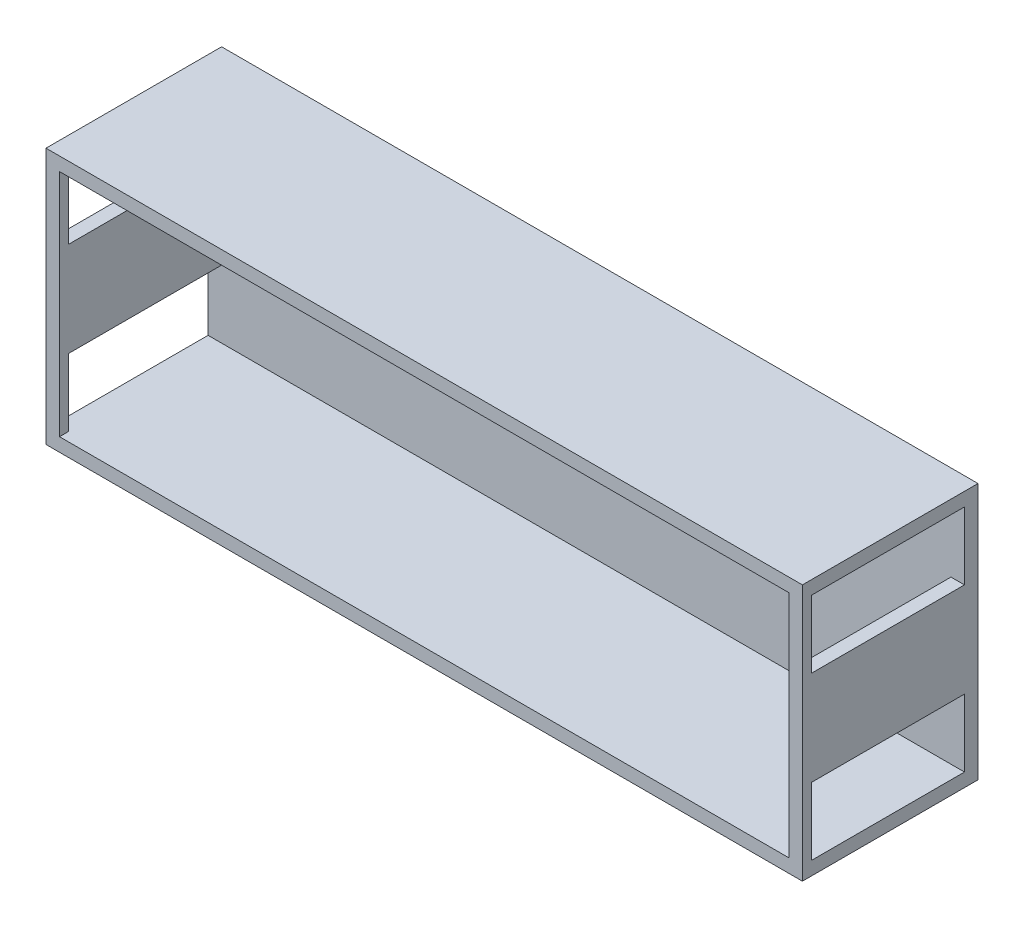
SolidWorks part; units mm, degrees
ref_plane "Front Plane" through (0, 0, 0) normal (0, 0, 1) x (1, 0, 0)
ref_plane "Top Plane" through (0, 0, 0) normal (0, 1, 0) x (1, 0, 0)
ref_plane "Right Plane" through (0, 0, 0) normal (1, 0, 0) x (0, 0, -1)
sketch "Sketch1" plane through (0, 0, 0) normal (0, 0, 1) x (1, 0, 0)
  line L1 (0, 0) -> (112, 0)
  line L2 (0, 0) -> (0, 38)
  line L3 (0, 38) -> (112, 38)
  line L4 (112, 0) -> (112, 38)
  dimension "D1" = 38
  dimension "D2" = 112
extrude "Boss-Extrude1" add sketch "Sketch1" along normal blind 26
shell "Shell1" thickness 2
sketch "Sketch4" plane through (0, 0, 0) normal (0, -1, 0) x (1, 0, 0)
  text T0 "GROOTBOT" font "Conthrax Sb" height in points 18
extrude "Cut-Extrude1" cut sketch "Sketch4" against normal blind 1
sketch "Sketch5" plane through (0, 0, 0) normal (-1, 0, 0) x (0, 0, 1)
  line L0 (26, 38) -> (0, 38) construction
  line L1 (24.6525, 36) -> (2, 36)
  line L2 (24.6525, 36) -> (24.6525, 26)
  line L3 (24.6525, 26) -> (2, 26)
  line L4 (2, 36) -> (2, 26)
  line L5 (26, 0) -> (0, 0) construction
  line L6 (24.6525, 2) -> (2, 2)
  line L7 (24.6525, 2) -> (24.6525, 12)
  line L8 (24.6525, 12) -> (2, 12)
  line L9 (2, 2) -> (2, 12)
  line L10 (0, 38) -> (0, 0) construction
  dimension "D1" = 2
  dimension "D2" = 10
  dimension "D3" = 10
  dimension "D4" = 2
  dimension "D5" = 2
  dimension "D6" = 2
extrude "Cut-Extrude2" cut sketch "Sketch5" against normal through all
sketch "Sketch6" plane through (0, 0, 0) normal (0, 0, -1) x (-1, 0, 0)
  line L0 (-56, 38) -> (-56, -6.2051) construction
  line L1 (-112, 38) -> (0, 38) construction
  line L2 (0, 19) -> (-112, 19) construction
  line L3 (0, 38) -> (0, 0) construction
  line L4 (-112, 0) -> (-112, 38) construction
  circle A2 centre (-28.2654, 19) radius 1.5
  circle A3 centre (-83.7346, 19) radius 1.5
extrude "Cut-Extrude3" cut sketch "Sketch6" against normal blind 10
